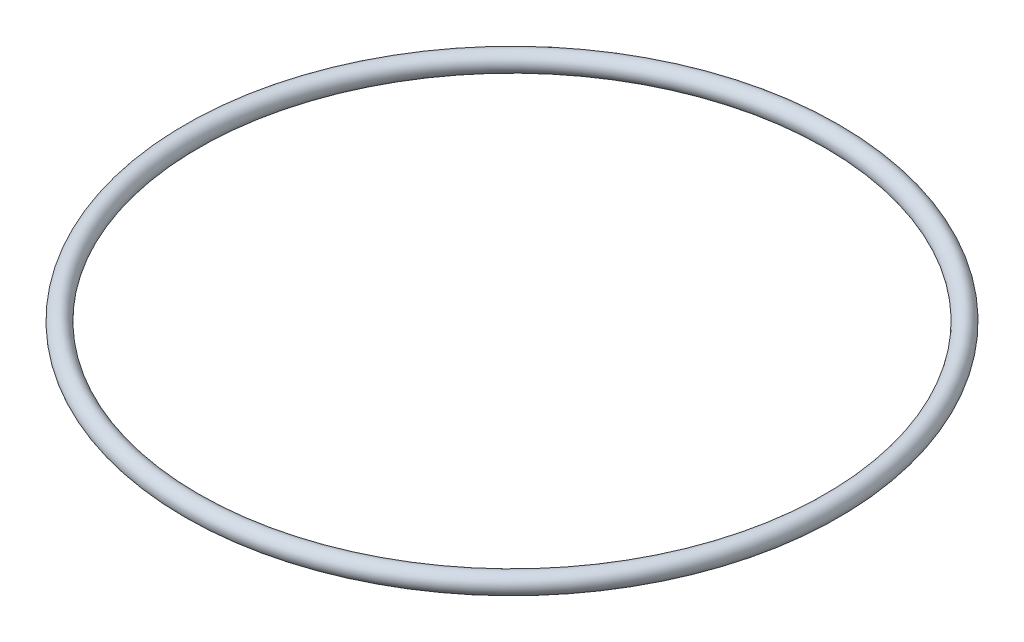
SolidWorks part; units mm, degrees
ref_plane "Plan de face" through (0, 0, 0) normal (0, 0, 1) x (1, 0, 0)
ref_plane "Plan de dessus" through (0, 0, 0) normal (0, 1, 0) x (1, 0, 0)
ref_plane "Plan de droite" through (0, 0, 0) normal (1, 0, 0) x (0, 0, -1)
sketch "Esquisse1" plane through (0, 0, 0) normal (0, 0, 1) x (1, 0, 0)
  line L0 (0, 0) -> (-336, 0) construction
  line L1 (-336, 0) -> (-336, 129.3523) construction
  circle A0 centre (0, 0) radius 10
  dimension "D1" = 336
  dimension "D2" = 20
revolve "Révolution1" add sketch "Esquisse1" angle 360 about L1
